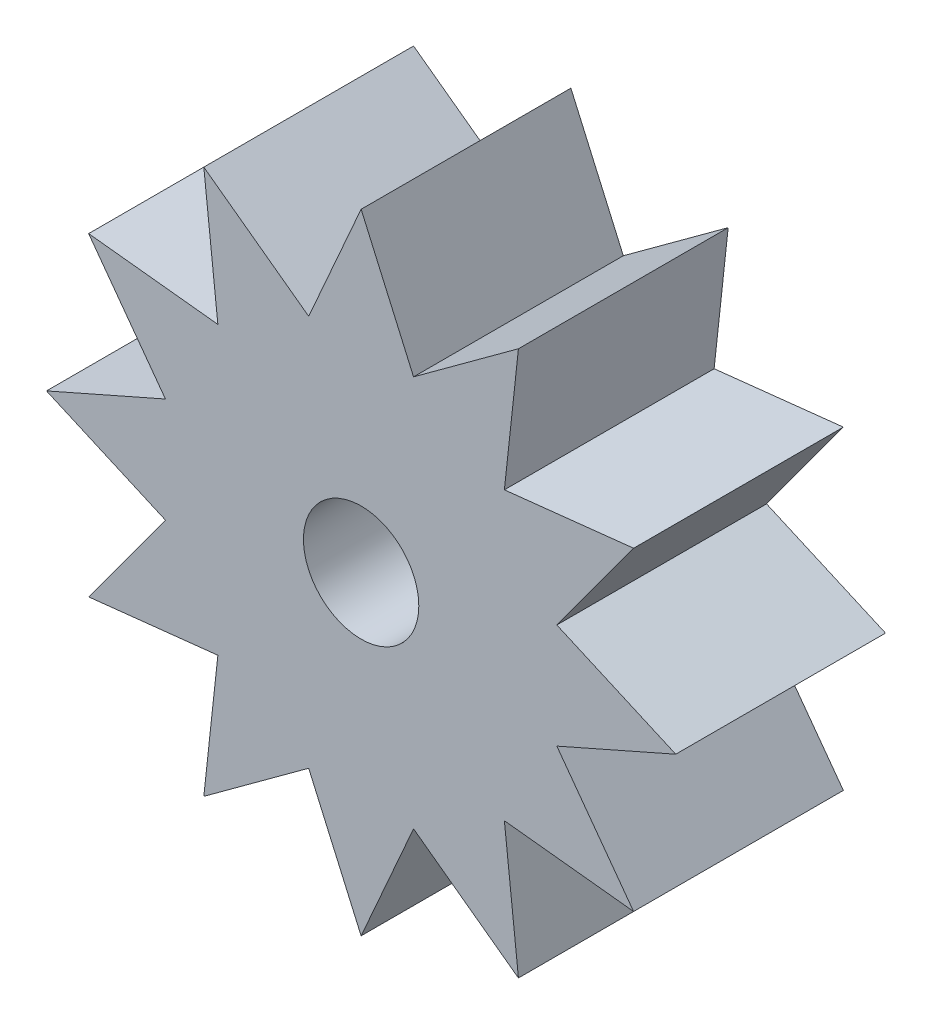
SolidWorks part; units mm, degrees
ref_plane "Front Plane" through (0, 0, 0) normal (0, 0, 1) x (1, 0, 0)
ref_plane "Top Plane" through (0, 0, 0) normal (0, 1, 0) x (1, 0, 0)
ref_plane "Right Plane" through (0, 0, 0) normal (1, 0, 0) x (0, 0, -1)
sketch "Sketch1" plane through (0, 0, 0) normal (0, 0, 1) x (1, 0, 0)
  line L0 (0, -15) -> (2.5, -9.3301)
  line L1 (0, -15) -> (-2.5, -9.3301)
  line L2 (-2.5, -9.3301) -> (2.5, -9.3301) construction
  line L3 (-7.5, -12.9904) -> (-2.5, -9.3301)
  line L4 (-7.5, -12.9904) -> (-6.8301, -6.8301)
  line L5 (-12.9904, -7.5) -> (-6.8301, -6.8301)
  line L6 (-12.9904, -7.5) -> (-9.3301, -2.5)
  line L7 (-15, 0) -> (-9.3301, -2.5)
  line L8 (-15, 0) -> (-9.3301, 2.5)
  line L9 (-12.9904, 7.5) -> (-9.3301, 2.5)
  line L10 (-12.9904, 7.5) -> (-6.8301, 6.8301)
  line L11 (-7.5, 12.9904) -> (-6.8301, 6.8301)
  line L12 (-7.5, 12.9904) -> (-2.5, 9.3301)
  line L13 (0, 15) -> (-2.5, 9.3301)
  line L14 (0, 15) -> (2.5, 9.3301)
  line L15 (7.5, 12.9904) -> (2.5, 9.3301)
  line L16 (7.5, 12.9904) -> (6.8301, 6.8301)
  line L17 (12.9904, 7.5) -> (6.8301, 6.8301)
  line L18 (12.9904, 7.5) -> (9.3301, 2.5)
  line L19 (15, 0) -> (9.3301, 2.5)
  line L20 (15, 0) -> (9.3301, -2.5)
  line L21 (12.9904, -7.5) -> (9.3301, -2.5)
  line L22 (12.9904, -7.5) -> (6.8301, -6.8301)
  line L23 (7.5, -12.9904) -> (6.8301, -6.8301)
  line L24 (7.5, -12.9904) -> (2.5, -9.3301)
  line L25 (-15, 0) -> (15, 0) construction
  line L26 (0, -15) -> (0, 15) construction
  circle A0 centre (0, 0) radius 2.75
  point P2 (0, -9.3301)
  point P41 (0, 0)
  dimension "D2" = 5.5
  dimension "D1" = 15
  dimension "D3" = 5
  dimension "D4" = 12
extrude "Boss-Extrude1" add sketch "Sketch1" along normal blind 10 contours L24 L23 L22 L21 L20 L19 L18 L17 L16 L15 L14 L13 L12 L11 L10 L9 L8 L7 L6 L5 L4 L3 L1 L0 A0
